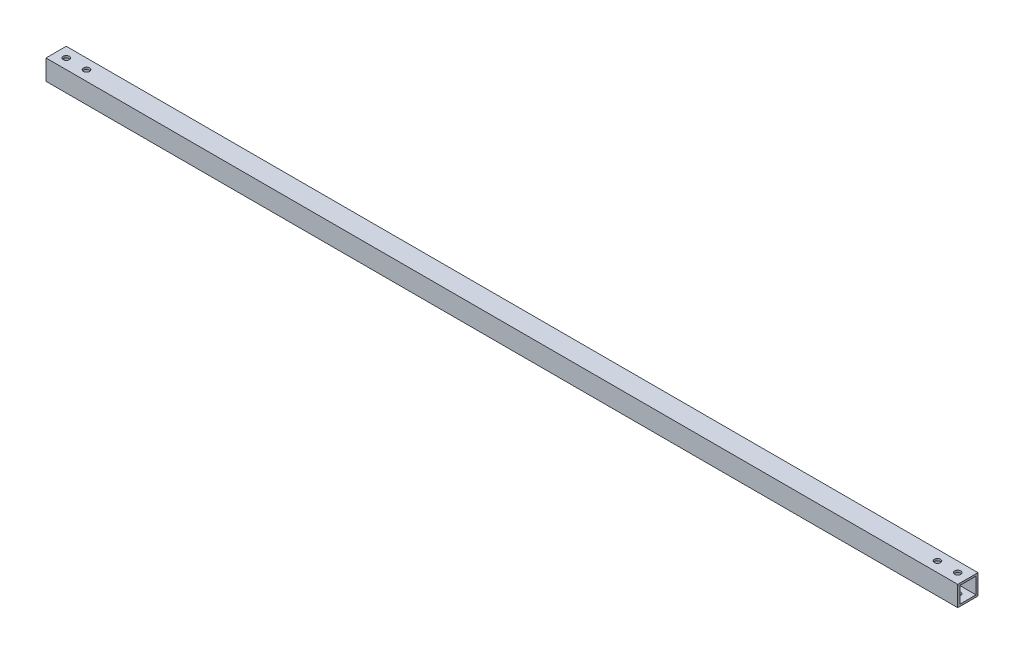
SolidWorks part; units mm, degrees
material "1060 Alloy"
ref_plane "Front Plane" through (0, 0, 0) normal (0, 0, 1) x (1, 0, 0)
ref_plane "Top Plane" through (0, 0, 0) normal (0, 1, 0) x (1, 0, 0)
ref_plane "Right Plane" through (0, 0, 0) normal (1, 0, 0) x (0, 0, -1)
sketch "Sketch1" plane through (0, 0, 0) normal (1, 0, 0) x (0, 0, -1)
  line L0 (8, 8) -> (-8, 8)
  line L1 (-8, 8) -> (-8, -8)
  line L2 (0, 0) -> (0, 27.1676) construction
  line L3 (0, 0) -> (-28.5263, 0) construction
  line L4 (8, 8) -> (8, -8)
  line L5 (8, -8) -> (-8, -8)
  line L7 (-10, 10) -> (10, 10)
  line L8 (-10, 10) -> (-10, -10)
  line L9 (-10, -10) -> (10, -10)
  line L10 (10, 10) -> (10, -10)
  point P8 (0, 8)
  point P11 (8, 0)
  point P12 (-8, 0)
  dimension "D1" = 16
  dimension "D2" = 20
  dimension "D3" = 10
  dimension "D4" = 10
extrude "Boss-Extrude1" add sketch "Sketch1" along normal mid plane 900
sketch "Sketch2" plane through (0, 10, 0) normal (0, 1, 0) x (1, 0, 0)
  line L0 (0, 0) -> (475.9786, 0) construction
  line L1 (450, 10) -> (450, -10) construction
  line L2 (-450, 10) -> (-450, -10) construction
  circle A0 centre (420, 0) radius 3
  circle A1 centre (440, 0) radius 3
  circle A2 centre (-440, 0) radius 3
  circle A3 centre (-420, 0) radius 3
  dimension "D1" = 6
  dimension "D2" = 20
  dimension "D3" = 10
  dimension "D4" = 20
  dimension "D5" = 10
extrude "Cut-Extrude1" cut sketch "Sketch2" against normal through all
